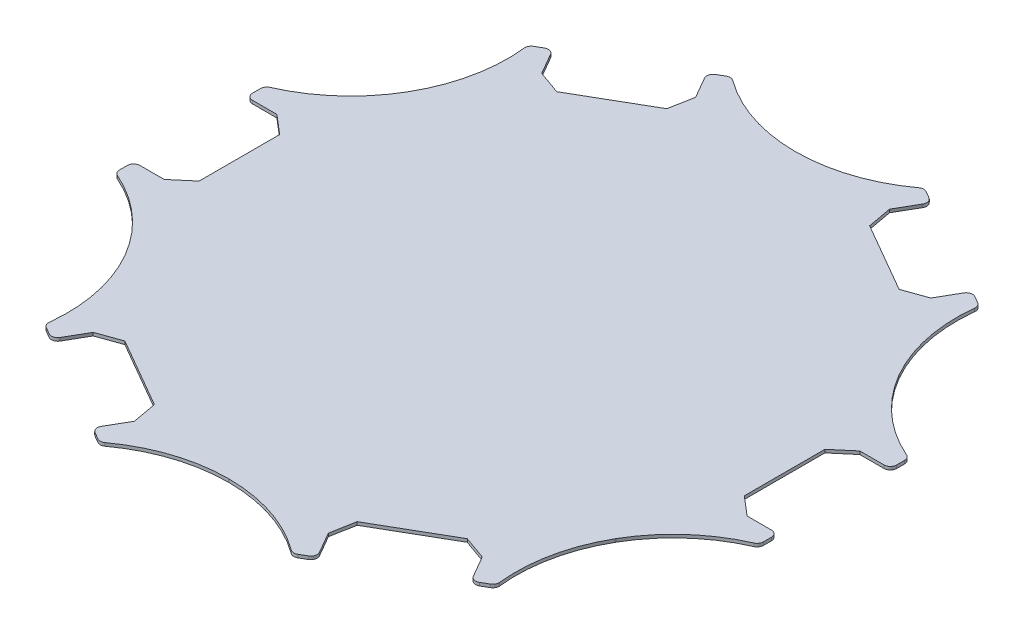
SolidWorks part; units mm, degrees
material "Perspex (TM) GS Acrylic Cast Sheet"
ref_plane "Front Plane" through (0, 0, 0) normal (0, 0, 1) x (1, 0, 0)
ref_plane "Top Plane" through (0, 0, 0) normal (0, 1, 0) x (1, 0, 0)
ref_plane "Right Plane" through (0, 0, 0) normal (1, 0, 0) x (0, 0, -1)
sketch "Sketch2" plane through (0, 0, 0) normal (0, 1, 0) x (1, 0, 0)
  line L1 (0, 125) -> (-58.0814, 125)
  line L2 (-35.5814, 86.0289) -> (-56.7125, 73.8289)
  line L3 (-79.2125, 112.8) -> (-108.2532, 62.5)
  line L4 (-35.5814, 86.0289) -> (-58.0814, 125)
  line L7 (0, 0) -> (0, 125)
  line L8 (0, 0) -> (-108.2532, 62.5)
  line L12 (-79.2125, 112.8) -> (-56.7125, 73.8289)
  circle A0 centre (-37.3857, 81.754) radius 1.35
  circle A1 centre (-52.1082, 73.254) radius 1.35
  circle A2 centre (-60.8873, 75.4599) radius 1.35
  circle A3 centre (-34.9066, 90.4599) radius 1.35
  circle A4 centre (-51.9066, 119.9048) radius 1.35
  circle A5 centre (-43.4066, 105.1824) radius 1.35
  circle A6 centre (-69.3873, 90.1824) radius 1.35
  circle A7 centre (-77.8873, 104.9048) radius 1.35
  dimension "D3" = 3.5
  dimension "D5" = 2.8
  dimension "D9" = 34
  dimension "D13" = 2.8
  dimension "D14" = 2.8
  dimension "D2" = 3.5
  dimension "D4" = 17
  dimension "D12" = 17
  dimension "D15" = 17
  dimension "D16" = 34
extrude "Boss-Extrude1" add sketch "Sketch2" along normal blind 1
pattern_circular "CirPattern1" count 6 every 60 about axis through (0, 0, 0) along (0, 1, 0) of "Boss-Extrude1"
sketch "Sketch4" plane through (0, 1, 0) normal (0, 1, 0) x (1, 0, 0)
  line L0 (58.0814, 125) -> (-58.0814, 125) construction
  line L1 (137.2939, 12.2) -> (79.2125, 112.8) construction
  line L2 (79.2125, -112.8) -> (137.2939, -12.2) construction
  line L3 (-58.0814, -125) -> (58.0814, -125) construction
  line L4 (-137.2939, -12.2) -> (-79.2125, -112.8) construction
  line L5 (-79.2125, 112.8) -> (-137.2939, 12.2) construction
  line L6 (79.2125, -112.8) -> (137.2939, -12.2)
  line L8 (137.2939, 12.2) -> (79.2125, 112.8)
  line L10 (58.0814, 125) -> (-58.0814, 125)
  line L12 (-79.2125, 112.8) -> (-137.2939, 12.2)
  line L14 (-92.2939, -12.2) -> (-137.2939, -12.2) construction
  line L15 (-137.2939, -12.2) -> (-79.2125, -112.8)
  line L17 (-58.0814, -125) -> (58.0814, -125)
  arc A0 (-30.9451, 108.6476) -> (30.9451, 108.6476) centre (0, 125) ccw
  arc A1 (78.619, 81.123) -> (109.5641, 27.5246) centre (108.2532, 62.5) ccw
  arc A2 (109.5641, -27.5246) -> (78.619, -81.123) centre (108.2532, -62.5) ccw
  arc A4 (-78.619, -81.123) -> (-109.5641, -27.5246) centre (-108.2532, -62.5) ccw
  arc A5 (-109.5641, 27.5246) -> (-78.619, 81.123) centre (-108.2532, 62.5) ccw
  arc A6 (58.0814, 125) -> (30.9451, 108.6476) centre (58.0814, 94.3078) ccw
  arc A7 (-30.9451, 108.6476) -> (-58.0814, 125) centre (-58.0814, 94.3078) ccw
  arc A8 (-79.2125, 112.8) -> (-78.619, 81.123) centre (-52.6322, 97.4539) ccw
  arc A9 (-109.5641, 27.5246) -> (-137.2939, 12.2) centre (-110.7137, -3.1461) ccw
  arc A10 (109.5641, -27.5246) -> (137.2939, -12.2) centre (110.7137, 3.1461) ccw
  arc A11 (-58.0814, -125) -> (-30.9451, -108.6476) centre (-58.0814, -94.3078) ccw
  arc A12 (-78.619, -81.123) -> (-79.2125, -112.8) centre (-52.6322, -97.4539) ccw
  arc A13 (-137.2939, -12.2) -> (-109.5641, -27.5246) centre (-110.7137, 3.1461) ccw
  arc A14 (78.619, 81.123) -> (79.2125, 112.8) centre (52.6322, 97.4539) ccw
  arc A16 (79.2125, -112.8) -> (78.619, -81.123) centre (52.6322, -97.4539) ccw
  arc A19 (137.2939, 12.2) -> (109.5641, 27.5246) centre (110.7137, -3.1461) ccw
  arc A20 (30.9451, -108.6476) -> (-30.9451, -108.6476) centre (0, -125) ccw
  arc A21 (30.9451, -108.6476) -> (58.0814, -125) centre (58.0814, -94.3078) ccw
extrude "Cut-Extrude3" cut sketch "Sketch4" against normal blind 5
sketch "Sketch8" plane through (0, 1, 0) normal (0, 1, 0) x (1, 0, 0)
  line L0 (-57.6659, 125.0058) -> (58.0814, 125)
  line L1 (79.4252, 112.443) -> (137.2939, 12.2)
  line L2 (137.0912, -12.5628) -> (79.2125, -112.8001)
  line L3 (57.6659, -125.0058) -> (-58.0814, -125.0001)
  line L4 (-79.4252, -112.4431) -> (-137.2939, -12.2001)
  line L5 (-137.0912, 12.5627) -> (-79.2125, 112.8)
  arc A0 (-44.3583, 116.9274) -> (44.3583, 116.9275) centre (0, 140) ccw
  arc A1 (-30.9451, 108.6476) -> (30.9451, 108.6476) centre (0, 125) ccw construction
  arc A2 (-44.3583, 116.9274) -> (-57.6644, 125.0058) centre (-57.6659, 110.0056) ccw
  arc A3 (58.0814, 125) -> (44.3583, 116.9275) centre (57.6658, 110.0057) ccw
  arc A4 (79.083, 96.8791) -> (79.426, 112.4417) centre (66.4347, 104.9429) ccw
  arc A5 (79.083, 96.8791) -> (123.4414, 20.0483) centre (121.2436, 70) ccw
  arc A6 (137.2939, 12.2) -> (123.4414, 20.0483) centre (124.1007, 5.0628) ccw
  arc A7 (123.4413, -20.0484) -> (137.0904, -12.5641) centre (124.1006, -5.0627) ccw
  arc A8 (123.4413, -20.0484) -> (79.0831, -96.8792) centre (121.2436, -70.0001) ccw
  arc A9 (79.2125, -112.8001) -> (79.0831, -96.8792) centre (66.4349, -104.943) ccw
  arc A10 (44.3583, -116.9275) -> (57.6644, -125.0058) centre (57.6659, -110.0056) ccw
  arc A11 (44.3583, -116.9275) -> (-44.3583, -116.9276) centre (0, -140.0001) ccw
  arc A12 (-58.0814, -125.0001) -> (-44.3583, -116.9276) centre (-57.6658, -110.0058) ccw
  arc A13 (-79.083, -96.8792) -> (-79.426, -112.4418) centre (-66.4347, -104.943) ccw
  arc A14 (-79.083, -96.8792) -> (-123.4414, -20.0484) centre (-121.2436, -70.0001) ccw
  arc A15 (-137.2939, -12.2001) -> (-123.4414, -20.0484) centre (-124.1007, -5.0629) ccw
  arc A16 (-123.4413, 20.0483) -> (-137.0904, 12.564) centre (-124.1006, 5.0626) ccw
  arc A17 (-123.4413, 20.0483) -> (-79.0831, 96.8792) centre (-121.2436, 70) ccw
  arc A18 (-79.2125, 112.8) -> (-79.0831, 96.8792) centre (-66.4349, 104.9429) ccw
  point P56 (0, 0)
  dimension "D1" = 6
extrude "Cut-Extrude9" cut sketch "Sketch8" against normal blind 10 contours A18 L5 A16 A17 | A15 L4 A13 A14 | A12 L3 A10 A11 | A9 L2 A7 A8 | A6 L1 A4 A5 | A3 L0 A2 A0
sketch "Sketch10" plane through (0, 1, 0) normal (0, 1, 0) x (1, 0, 0)
  circle A0 centre (0, 0) radius 24.4942 construction
  point P4 (0, 0)
sketch "Sketch9" plane through (0, 1, 0) normal (0, 1, 0) x (1, 0, 0)
  line L0 (86.5939, 12.8) -> (92.5949, 17.9)
  line L1 (102.2939, -17.9) -> (102.2939, -27.4077)
  line L2 (102.2939, -27.4077) -> (142.4909, -27.4077)
  line L3 (102.2939, 17.9) -> (102.2939, 27.4955)
  line L4 (102.2939, 27.4955) -> (142.4909, 27.4955)
  line L5 (86.5939, -12.8) -> (92.5949, -17.9)
  line L6 (142.4909, 27.4955) -> (142.4909, -27.4077)
  line L9 (86.5939, 12.8) -> (86.5939, -12.8)
  line L10 (92.5949, -17.9) -> (102.2939, -17.9)
  line L12 (102.2939, 17.9) -> (92.5949, 17.9)
  line L13 (92.2939, -12.2) -> (92.2939, 12.2) construction
  line L14 (92.2939, 12.2) -> (137.2939, 12.2) construction
  line L15 (137.2939, -12.2) -> (92.2939, -12.2) construction
  line L65 (95.0573, -109.653) -> (47.5097, -137.1046)
  line L66 (27.4112, -102.2929) -> (47.5097, -137.1046)
  line L67 (35.6451, -97.5391) -> (27.4112, -102.2929)
  line L68 (30.7956, -89.1395) -> (35.6451, -97.5391)
  line L69 (32.2118, -81.3925) -> (30.7956, -89.1395)
  line L70 (54.3821, -68.5925) -> (32.2118, -81.3925)
  line L71 (54.3821, -68.5925) -> (61.7993, -71.2395)
  line L72 (66.6488, -79.6391) -> (61.7993, -71.2395)
  line L73 (66.6488, -79.6391) -> (74.9588, -74.8413)
  line L74 (74.9588, -74.8413) -> (95.0573, -109.653)
  line L76 (-47.4336, -137.1485) -> (-94.9812, -109.6969)
  line L77 (-74.8827, -74.8853) -> (-94.9812, -109.6969)
  line L78 (-66.6488, -79.6391) -> (-74.8827, -74.8853)
  line L79 (-61.7993, -71.2395) -> (-66.6488, -79.6391)
  line L80 (-54.3821, -68.5925) -> (-61.7993, -71.2395)
  line L81 (-32.2118, -81.3925) -> (-54.3821, -68.5925)
  line L82 (-32.2118, -81.3925) -> (-30.7956, -89.1395)
  line L83 (-35.6451, -97.5391) -> (-30.7956, -89.1395)
  line L84 (-35.6451, -97.5391) -> (-27.3351, -102.3369)
  line L85 (-27.3351, -102.3369) -> (-47.4336, -137.1485)
  line L87 (-142.4909, -27.4955) -> (-142.4909, 27.4077)
  line L88 (-102.2939, 27.4077) -> (-142.4909, 27.4077)
  line L89 (-102.2939, 17.9) -> (-102.2939, 27.4077)
  line L90 (-92.5949, 17.9) -> (-102.2939, 17.9)
  line L91 (-86.5939, 12.8) -> (-92.5949, 17.9)
  line L92 (-86.5939, -12.8) -> (-86.5939, 12.8)
  line L93 (-86.5939, -12.8) -> (-92.5949, -17.9)
  line L94 (-102.2939, -17.9) -> (-92.5949, -17.9)
  line L95 (-102.2939, -17.9) -> (-102.2939, -27.4955)
  line L96 (-102.2939, -27.4955) -> (-142.4909, -27.4955)
  line L98 (-95.0573, 109.653) -> (-47.5097, 137.1046)
  line L99 (-27.4112, 102.2929) -> (-47.5097, 137.1046)
  line L100 (-35.6451, 97.5391) -> (-27.4112, 102.2929)
  line L101 (-30.7956, 89.1395) -> (-35.6451, 97.5391)
  line L102 (-32.2118, 81.3925) -> (-30.7956, 89.1395)
  line L103 (-54.3821, 68.5925) -> (-32.2118, 81.3925)
  line L104 (-54.3821, 68.5925) -> (-61.7993, 71.2395)
  line L105 (-66.6488, 79.6391) -> (-61.7993, 71.2395)
  line L106 (-66.6488, 79.6391) -> (-74.9588, 74.8413)
  line L107 (-74.9588, 74.8413) -> (-95.0573, 109.653)
  line L109 (47.4336, 137.1485) -> (94.9812, 109.6969)
  line L110 (74.8827, 74.8853) -> (94.9812, 109.6969)
  line L111 (66.6488, 79.6391) -> (74.8827, 74.8853)
  line L112 (61.7993, 71.2395) -> (66.6488, 79.6391)
  line L113 (54.3821, 68.5925) -> (61.7993, 71.2395)
  line L114 (32.2118, 81.3925) -> (54.3821, 68.5925)
  line L115 (32.2118, 81.3925) -> (30.7956, 89.1395)
  line L116 (35.6451, 97.5391) -> (30.7956, 89.1395)
  line L117 (35.6451, 97.5391) -> (27.3351, 102.3369)
  line L118 (27.3351, 102.3369) -> (47.4336, 137.1485)
  point P9 (86.5939, 0)
  point P76 (0.3751, 1)
  point P78 (0, 0)
  point P79 (0.452, 0.7829)
  point P85 (0, 0)
  dimension "D1" = 5.7
  dimension "D2" = 5.7
  dimension "D3" = 5.7
  dimension "D4" = 10
  dimension "D5" = 10
  dimension "D6" = 0.6
  dimension "D7" = 40.36
  dimension "D8" = 0.6
  dimension "D9" = 40.36
  dimension "D11" = 6
extrude "Cut-Extrude10" cut sketch "Sketch9" against normal through all
fillet "Fillet2" radius 2 24 edges at (102.2939, 0.5, -17.9) (102.2939, 0.5, -23.73) (102.2939, 0.5, 23.7301) (102.2939, 0.5, 17.9) (71.6978, 0.5, 76.7241) (66.6488, 0.5, 79.6391) (35.6451, 0.5, 97.5391) (30.5961, 0.5, 100.4542) (-30.5961, 0.5, 100.4542) (-35.6451, 0.5, 97.5391) (-66.6488, 0.5, 79.6391) (-71.6978, 0.5, 76.7241) (-102.2939, 0.5, 23.7301) (-102.2939, 0.5, 17.9) (-102.2939, 0.5, -17.9) (-102.2939, 0.5, -23.73) (-71.6978, 0.5, -76.7241) (-66.6488, 0.5, -79.6391) (-35.6451, 0.5, -97.5391) (-30.5961, 0.5, -100.4541) (30.5961, 0.5, -100.4541) (35.6451, 0.5, -97.5391) (66.6488, 0.5, -79.6391) (71.6978, 0.5, -76.7241)
